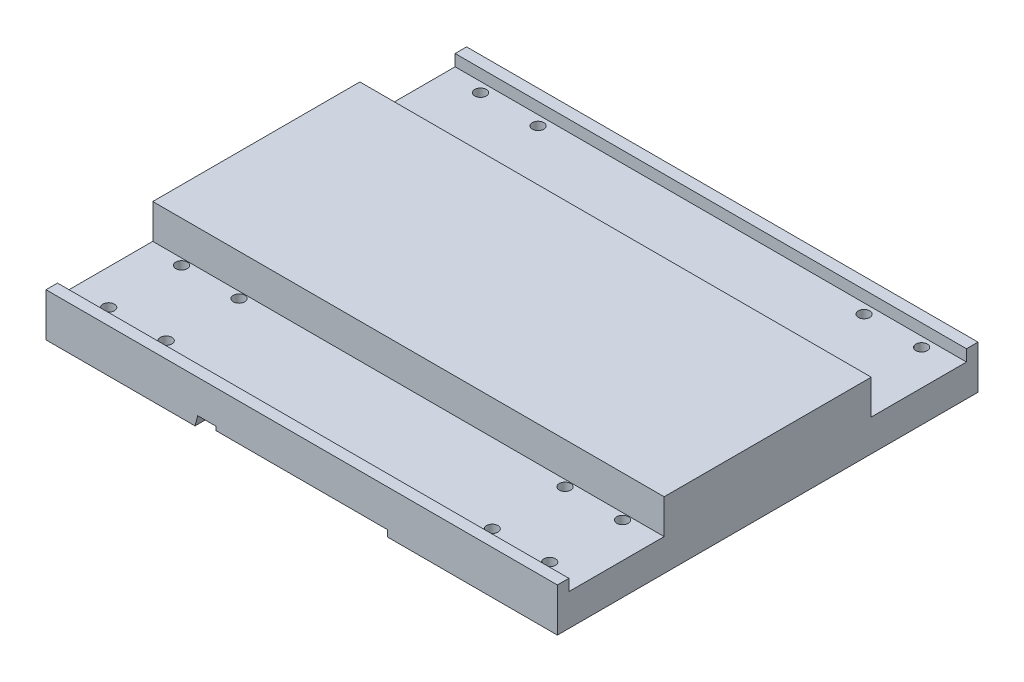
SolidWorks part; units mm, degrees
ref_plane "前视基准面" through (0, 0, 0) normal (0, 0, 1) x (1, 0, 0)
ref_plane "上视基准面" through (0, 0, 0) normal (0, 1, 0) x (1, 0, 0)
ref_plane "右视基准面" through (0, 0, 0) normal (1, 0, 0) x (0, 0, -1)
other "Configuration Table"
sketch "草图1" plane through (0, 0, 0) normal (0, 1, 0) x (1, 0, 0)
  line L1 (0, 0) -> (400, 0)
  line L2 (0, 0) -> (0, 329)
  line L3 (0, 329) -> (400, 329)
  line L4 (400, 0) -> (400, 329)
extrude "凸台-拉伸2" add sketch "草图1" along normal blind 25
sketch "草图2" plane through (0, 25, 0) normal (0, 1, 0) x (1, 0, 0)
  line L0 (0, 329) -> (0, 320)
  line L1 (0, 329) -> (0, 0) construction
  line L2 (0, 320) -> (400, 320)
  line L3 (400, 0) -> (400, 329) construction
  line L4 (400, 320) -> (400, 329)
  line L5 (400, 329) -> (0, 329)
  line L6 (0, 0) -> (0, 9)
  line L7 (0, 9) -> (400, 9)
  line L8 (400, 9) -> (400, 0)
  line L9 (0, 0) -> (400, 0) construction
  line L10 (400, 0) -> (0, 0)
extrude "凸台-拉伸3" add sketch "草图2" along normal blind 9
sketch "草图3" plane through (400, 0, 0) normal (1, 0, 0) x (0, 0, -1)
  line L0 (164.5, 25) -> (164.5, 52)
  line L1 (9, 25) -> (320, 25) construction
  line L2 (164.5, 52) -> (83.5, 52)
  line L3 (83.5, 52) -> (83.5, 25)
  line L4 (83.5, 25) -> (245.5, 25)
  line L5 (245.5, 25) -> (245.5, 52)
  line L6 (245.5, 52) -> (164.5, 52)
  line M6 (320, 25) -> (9, 25)
extrude "凸台-拉伸4" add sketch "草图3" against normal blind 400 contours L5 L6 L0 M6 | L2 L3 L0 M6
sketch "草图4" plane through (0, 0, 0) normal (0, -1, 0) x (1, 0, 0)
  line L0 (200, 0) -> (133, 0)
  line L1 (0, 0) -> (400, 0) construction
  line L2 (200, 0) -> (200, -5)
  line L3 (200, -5) -> (267.25, -5)
  line L4 (267.25, -5) -> (267.25, 0)
  line L5 (267.25, -5) -> (267.25, -329)
  line L6 (400, -329) -> (0, -329) construction
  line L7 (267.25, -329) -> (133, -329)
  line L8 (133, -329) -> (133, 0)
  line L9 (267.25, 0) -> (200, 0)
  line M3 (0, -329) -> (400, -329)
  line M5 (400, 0) -> (0, 0)
extrude "切除-拉伸1" cut sketch "草图4" against normal blind 5 contours L8 L5 L3 L2 M3 M5 | L3 L4 L2 M5
sketch "草图5" plane through (0, 0, 0) normal (0, 0, 1) x (1, 0, 0)
  line L0 (200, 34) -> (133, 34)
  line L1 (0, 34) -> (400, 34) construction
  line L2 (133, 34) -> (133, 5)
  line L3 (133, 0) -> (118.7, 0)
  line L4 (0, 0) -> (133, 0) construction
  line L5 (118.7, 0) -> (118.7, 8)
  line L6 (118.7, 8) -> (133, 8)
  line L7 (133, 8) -> (133, -0.5312)
  line L8 (133, -0.5312) -> (118.7, 0)
  line M8 (0, 0) -> (133, 0)
  line M9 (133, 0) -> (133, 5)
extrude "切除-拉伸2" cut sketch "草图5" against normal blind 400 contours L6 L5 L2 M8 M9
sketch "草图6" plane through (0, 0, 0) normal (0, 0, 1) x (1, 0, 0)
  line L0 (118.7, 8) -> (116.5564, 0)
  line L1 (0, 0) -> (118.7, 0) construction
  line L2 (116.5564, 0) -> (118.7, 0)
  line L3 (118.7, 0) -> (118.7, 8)
extrude "切除-拉伸3" cut sketch "草图6" against normal blind 400
sketch "草图8" plane through (0, 0, 0) normal (0, -1, 0) x (1, 0, 0)
  line L0 (400, 0) -> (372.5, 0)
  line L2 (267.25, 0) -> (400, 0) construction
  line L3 (372.5, 0) -> (372.5, -21.5)
  line L4 (372.5, -21.5) -> (327.5, -21.5)
  line L5 (327.5, -21.5) -> (327.5, -78.5)
  line L6 (327.5, -78.5) -> (372.5, -78.5)
  line L7 (400, 0) -> (0, 0)
  line L8 (200, 0) -> (200, -345.1353)
  circle A0 centre (372.5, -312.4) radius 4.5
  circle A1 centre (327.5, -312.4) radius 4.5
  circle A2 centre (372.5, -255.4) radius 4.5
  circle A3 centre (327.5, -255.4) radius 4.5
  circle A4 centre (372.5, -78.5) radius 4.5
  circle A5 centre (327.5, -78.5) radius 4.5
  circle A6 centre (372.5, -21.5) radius 4.5
  circle A7 centre (327.5, -21.5) radius 4.5
  circle A8 centre (27.5, -21.5) radius 4.5
  circle A9 centre (72.5, -21.5) radius 4.5
  circle A10 centre (72.5, -78.5) radius 4.5
  circle A11 centre (27.5, -78.5) radius 4.5
  circle A12 centre (72.5, -312.4) radius 4.5
  circle A13 centre (27.5, -312.4) radius 4.5
  circle A14 centre (27.5, -255.4) radius 4.5
  circle A15 centre (72.5, -255.4) radius 4.5
extrude "切除-拉伸4" cut sketch "草图8" against normal blind 400 contours A0 | A1 | A2 | A3 | A5 | A4 | A7 | A6 | A13 | A12 | A15 | A14 | A10 | A11 | A8 | A9
